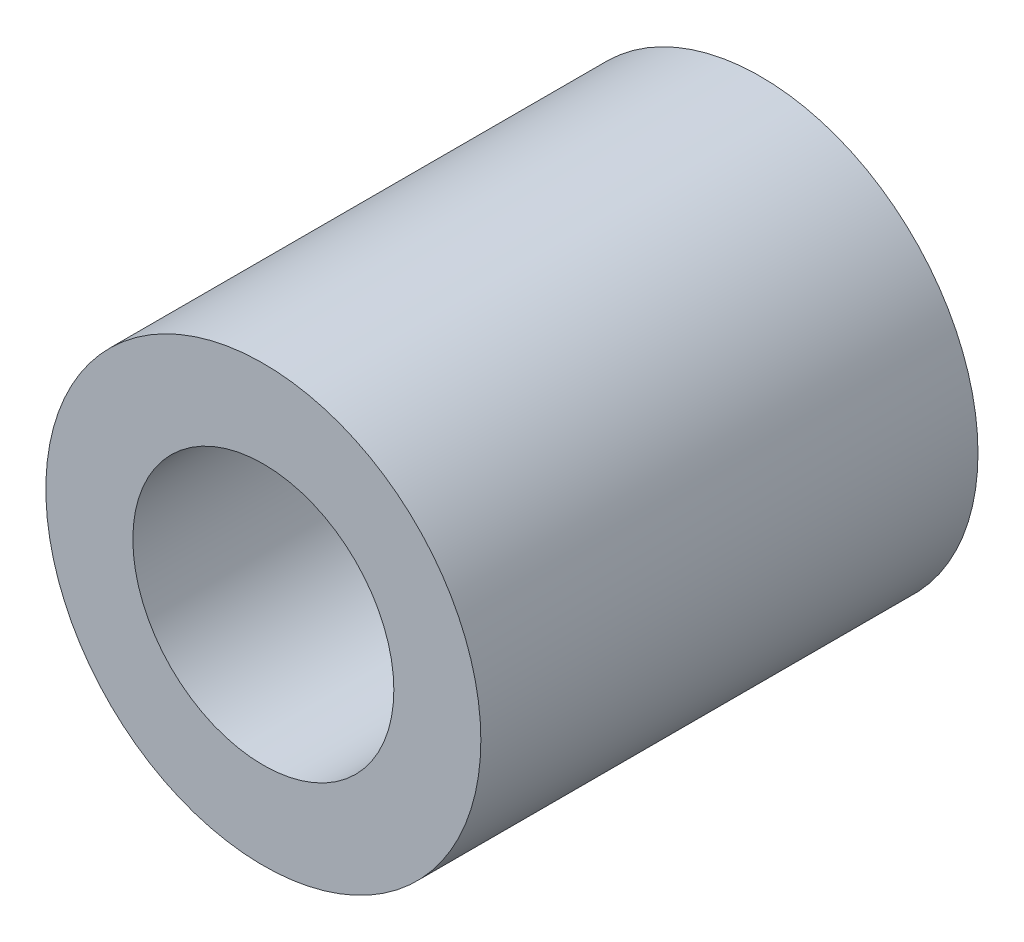
SolidWorks part; units mm, degrees
ref_plane "前视基准面" through (0, 0, 0) normal (0, 0, 1) x (1, 0, 0)
ref_plane "上视基准面" through (0, 0, 0) normal (0, 1, 0) x (1, 0, 0)
ref_plane "右视基准面" through (0, 0, 0) normal (1, 0, 0) x (0, 0, -1)
sketch "草图1" plane through (0, 0, 0) normal (0, 0, 1) x (1, 0, 0)
  circle A0 centre (0, 0) radius 3.5
  circle A1 centre (0, 0) radius 2.1
  dimension "D1" = 7
  dimension "D2" = 4.2
extrude "凸台-拉伸1" add sketch "草图1" along normal blind 8
